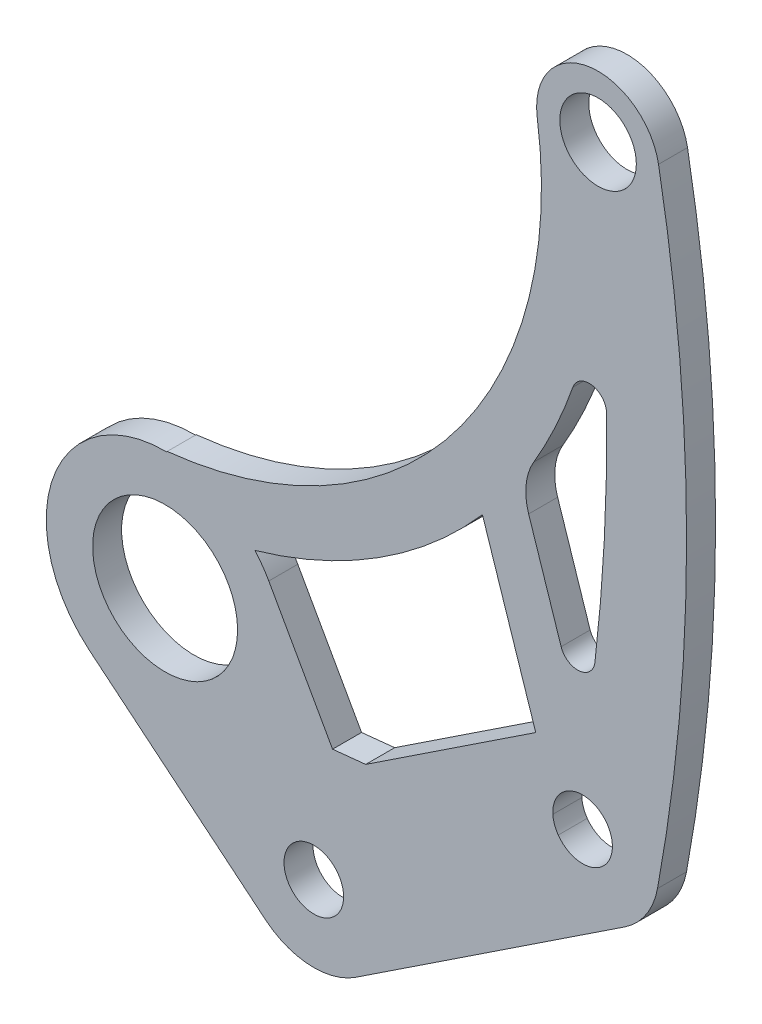
SolidWorks part; units mm, degrees
material "6061-T6 (SS)"
ref_plane "Front Plane" through (0, 0, 0) normal (0, 0, 1) x (1, 0, 0)
ref_plane "Top Plane" through (0, 0, 0) normal (0, 1, 0) x (1, 0, 0)
ref_plane "Right Plane" through (0, 0, 0) normal (1, 0, 0) x (0, 0, -1)
sketch "Sketch2" plane through (0, 0, 0) normal (0, 0, 1) x (1, 0, 0)
  line L0 (0, 0) -> (45.72, 0) construction
  line L1 (45.72, 0) -> (47.4133, 66.0183) construction
  line L2 (47.4133, 66.0183) -> (0, 0) construction
  line L3 (-9.9543, 8.3886) -> (42.2663, 70.3558)
  line L4 (54.1443, 66.0101) -> (54.0639, -0.0102)
  line L5 (46.5729, -8.3002) -> (1.3307, -12.9493)
  line L6 (-6.2268, 4.9225) -> (44.1256, 68.6173)
  line L7 (0.8114, -7.8959) -> (46.0536, -3.2468)
  line L8 (48.9813, -0.1295) -> (51.601, 65.852)
  line L9 (0, 0) -> (16.2847, -19.4928) construction
  line L10 (45.72, 0) -> (38.8832, 9.7026) construction
  line L11 (45.72, 0) -> (42.0108, 11.275) construction
  line L12 (45.72, 0) -> (44.9726, 11.8459) construction
  line L13 (47.2407, 59.2895) -> (45.9339, 8.3412)
  line L14 (45.72, 0) -> (36.8585, 26.9366) construction
  line L15 (34.7499, 24.3546) -> (40.5957, 6.585)
  line L16 (38.8824, 29.7758) -> (45.9339, 8.3412)
  line L17 (41.2892, 13.4683) -> (38.6201, 12.5902) construction
  line L18 (41.2892, 13.4683) -> (43.9584, 14.3464) construction
  line L19 (0, 0) -> (16.2847, -19.4928) construction
  line L20 (-8.2839, -10.0416) -> (10.9749, -25.9292)
  line L21 (50.3269, -6.9568) -> (20.8916, -26.4496)
  line L22 (11.3551, 6.3652) -> (23.563, -15.4129)
  line L23 (41.1131, 6.9568) -> (11.6777, -12.536)
  circle A0 centre (0, 0) radius 7.9375
  circle A1 centre (45.72, 0) radius 3.2639
  circle A2 centre (47.4133, 66.0183) radius 4.191
  circle A3 centre (0, 0) radius 13.0175
  circle A4 centre (45.72, 0) radius 8.3439
  circle A5 centre (47.4133, 66.0183) radius 6.731
  circle A8 centre (-4.5053, 58.5645) radius 45.72
  circle A9 centre (-4.5053, 58.5645) radius 52.07
  circle A10 centre (-133.3933, 33.155) radius 190.5
  circle A11 centre (-142.1385, 38.656) radius 190.5
  circle A13 centre (16.2847, -19.4928) radius 3.2639
  circle A14 centre (16.2847, -19.4928) radius 8.3439
  point P29 (47.2407, 59.2895)
  point P30 (45.72, 0)
  point P54 (0, 0)
  dimension "D1" = 8.382
  dimension "D2" = 6.5278
  dimension "D3" = 15.875
  dimension "D13" = 381
  dimension "D14" = 381
  dimension "D17" = 91.44
  dimension "D19" = 6.5278
  dimension "2.7" = 45.72
  dimension "D5" = 66.04
  dimension "D6" = 5.08
  dimension "D7" = 2.54
  dimension "D8" = 5.08
  dimension "D9" = 81.28
  dimension "D4" = 54.83
  dimension "D10" = 71.79
  dimension "D11" = 86.39
  dimension "D12" = 6.35
  dimension "D15" = 25.4
  dimension "D16" = 50.124
  dimension "D18" = 5.08
extrude "Boss-Extrude1" add sketch "Sketch2" along normal blind 3.175 contours A3 A9 L13 A5 L6 A8 | A4 A10 A5 L4 | A5 L8 A4 L4 | A11 A4 L8 A5 A9 | A11 A9 A5 | A9 A11 L13 | A9 A5 L8 A2 | A11 A5 A9 A2 | A9 A2 L8 A5 | A2 A11 A5 L6 | A11 A2 A9 A5 | A5 A11 A2 L6 | L6 A9 A0 A3 | A3 A9 L6 | A9 A3 L7 A0 L6 | A9 L6 A0 | A9 A0 L7 A3 | L5 A11 A4 L7 A3 | A11 L5 A4 | A11 A4 L8 A1 L7 | A4 A11 L7 | L7 A11 A1 A4 | A11 L7 A1 | A11 A1 L8 A4 | A8 L6 A5 | A9 L15 A4 L16 | A14 L23 L5 A3 L20 | A3 L5 L23 L22 L7 | A14 L5 L22 L23 | A14 L5 L23 | A14 L22 L5 | A3 L7 L22 | L23 L7 L22 | A4 L15 L23 L7 | A14 L21 A11 L5 L22 | L5 A14 | A14 L5 A13 | A11 L21 A4 L5 | A4 L23 L15
ref_plane "Plane2" through (45.72, 0, 0) normal (-0.576, 0.8174, 0) x (0.8174, 0.576, 0)
split line "Split Line2"
ref_plane "Plane3" through (45.72, 0, 0) normal (-0.063, 0.998, 0) x (0.998, 0.063, 0)
split line "Split Line3"
fillet "Fillet1" [suppressed] radius 2.54
fillet "Fillet2" [suppressed] radius 3.81
fillet "Fillet3" radius 1.905 2 edges at (45.9339, 8.3412, 1.5875) (47.5238, 56.5014, 1.5875)
fillet "Fillet4" radius 6.35 1 edges at (38.8824, 29.7758, 1.5875)
equation "\"Droop angle\"= 54.83"
equation "\"Static angle\"= 71.79"
equation "\"Jounce angle\"= 86.39"
equation "\"D4@Sketch2\"=\"Droop angle\""
equation "\"D10@Sketch2\"=\"Static angle\""
equation "\"D11@Sketch2\"=\"Jounce angle\""
equation "\"DL Rocker Angle\"= 50.124deg"
equation "\"DL Rocker Length\"= 1.0in"
equation "\"D15@Sketch2\"=\"DL Rocker Length\""
